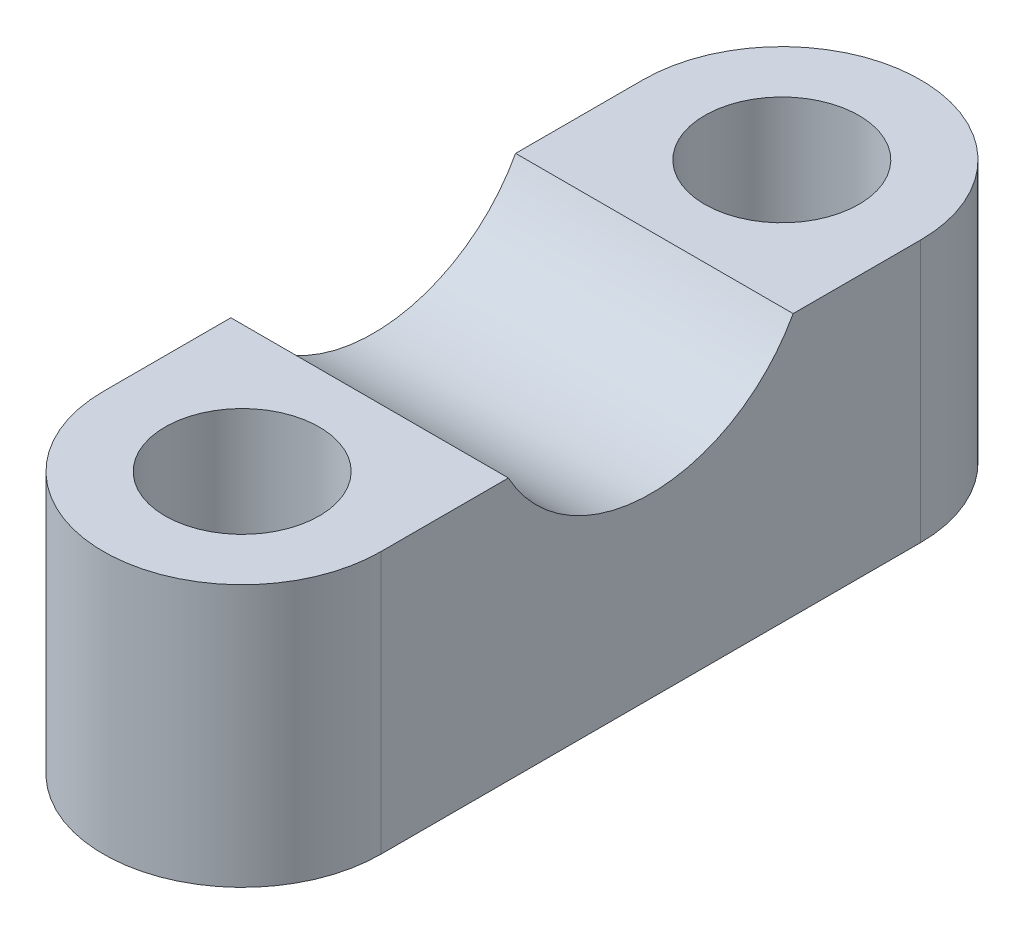
SolidWorks part; units mm, degrees
ref_plane "Front Plane" through (0, 0, 0) normal (0, 0, 1) x (1, 0, 0)
ref_plane "Top Plane" through (0, 0, 0) normal (0, 1, 0) x (1, 0, 0)
ref_plane "Right Plane" through (0, 0, 0) normal (1, 0, 0) x (0, 0, -1)
sketch "Sketch1" plane through (0, 0, 0) normal (0, 1, 0) x (1, 0, 0)
  line L0 (-38, 0) -> (-38, 35)
  line L1 (-56, 0) -> (-56, 35)
  arc A0 (-56, 0) -> (-38, 0) centre (-47, 0) ccw
  arc A1 (-38, 35) -> (-56, 35) centre (-47, 35) ccw
  circle A2 centre (-47, 35) radius 5
  circle A3 centre (-47, 0) radius 5
  dimension "D2" = 18
  dimension "D1" = 10
  dimension "D4" = 10
  dimension "D3" = 2
extrude "Boss-Extrude1" add sketch "Sketch1" along normal blind 17
sketch "Sketch2" plane through (0, 0, 0) normal (1, 0, 0) x (0, 0, -1)
  line L0 (0, 17) -> (35, 17) construction
  circle A0 centre (17.5, 22) radius 10.5
  point P4 (17.5, 17)
  dimension "D1" = 21
  dimension "D2" = 5
extrude "Cut-Extrude1" cut sketch "Sketch2" against normal blind 64 contours A0
sketch "Sketch3" plane through (0, 0, 0) normal (0, -1, 0) x (1, 0, 0)
  line L0 (-52, -7.4833) -> (-52, -27.5167)
  line L2 (-47, 1.1161) -> (-47, -35) construction
  line L3 (-42, -7.4833) -> (-42, -27.5167)
  arc A0 (-52, -7.4833) -> (-42, -7.4833) centre (-47, 0) ccw
  arc A1 (-42, -27.5167) -> (-52, -27.5167) centre (-47, -35) ccw
extrude "Cut-Extrude2" cut sketch "Sketch3" against normal blind 8
